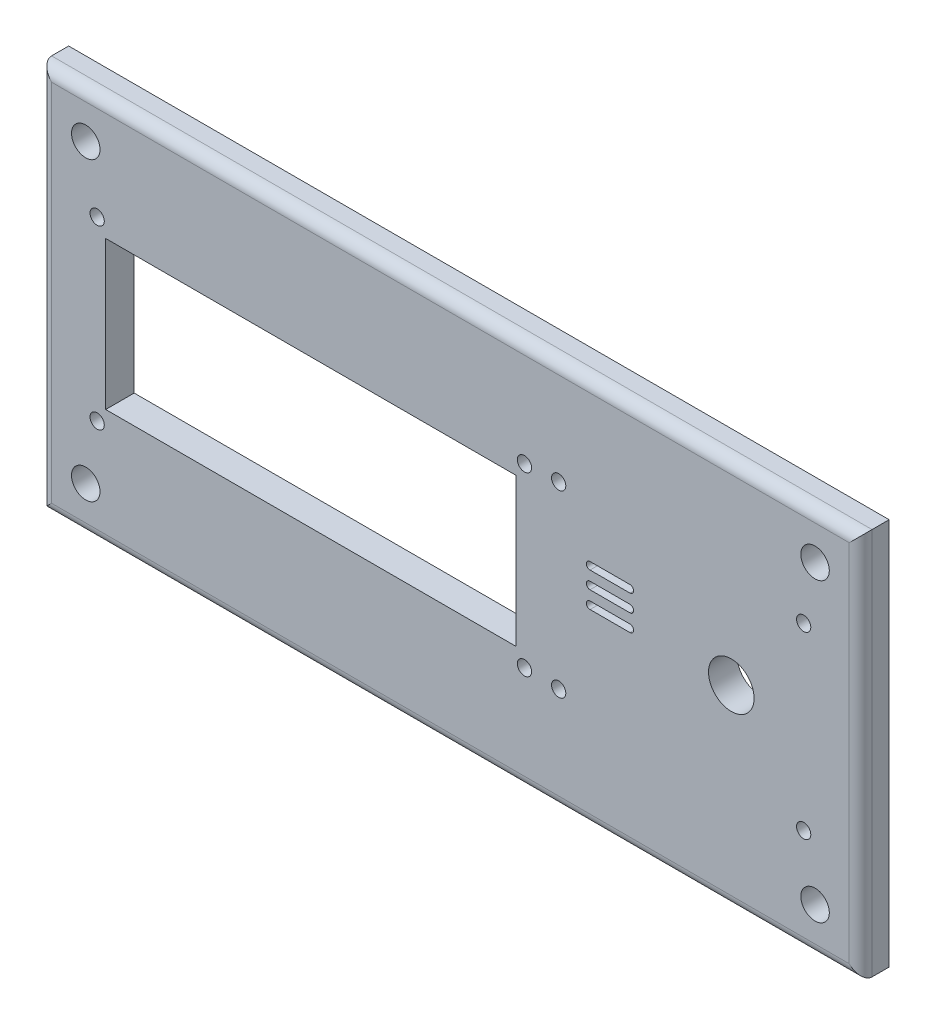
SolidWorks part; units mm, degrees
ref_plane "Спереди" through (0, 0, 0) normal (0, 0, 1) x (1, 0, 0)
ref_plane "Сверху" through (0, 0, 0) normal (0, 1, 0) x (1, 0, 0)
ref_plane "Справа" through (0, 0, 0) normal (1, 0, 0) x (0, 0, -1)
sketch "Эскиз1" plane through (0, 0, 0) normal (0, 0, 1) x (1, 0, 0)
  line L1 (-68.9586, 25.5843) -> (75.0414, 25.5843)
  line L2 (-68.9586, 25.5843) -> (-68.9586, -42.4157)
  line L3 (-68.9586, -42.4157) -> (75.0414, -42.4157)
  line L4 (75.0414, 25.5843) -> (75.0414, -42.4157)
  dimension "D1" = 144
  dimension "D2" = 68
extrude "Бобышка-Вытянуть1" add sketch "Эскиз1" along normal blind 5
sketch "Эскиз2" plane through (0, 0, 5) normal (0, 0, 1) x (1, 0, 0)
  line L0 (75.0414, 25.5843) -> (-68.9586, 25.5843) construction
  line L3 (-68.9586, 25.5843) -> (-68.9586, -42.4157) construction
  circle A0 centre (-58.9586, 7.0843) radius 1.25
  circle A1 centre (-58.9586, -23.9157) radius 1.25
  circle A2 centre (16.0414, 7.0843) radius 1.25
  circle A3 centre (16.0414, -23.9157) radius 1.25
  dimension "D1" = 2.5
  dimension "D2" = 2.5
  dimension "D3" = 2.5
  dimension "D4" = 2.5
  dimension "D5" = 75
  dimension "D6" = 31
  dimension "D7" = 31
  dimension "D8" = 75
  dimension "D9" = 18.5
  dimension "D10" = 10
  dimension "D11" = 10
  dimension "D12" = 18.5
extrude "Вырез-Вытянуть1" cut sketch "Эскиз2" against normal through all
sketch "Эскиз3" plane through (0, 0, 5) normal (0, 0, 1) x (1, 0, 0)
  line L0 (75.0414, 25.5843) -> (-68.9586, 25.5843) construction
  line L1 (-57.4586, 4.5843) -> (14.5414, 4.5843)
  line L2 (-57.4586, 4.5843) -> (-57.4586, -21.4157)
  line L3 (-57.4586, -21.4157) -> (14.5414, -21.4157)
  line L4 (14.5414, 4.5843) -> (14.5414, -21.4157)
  circle A1 centre (16.0414, 7.0843) radius 1.25 construction
  circle A3 centre (-58.9586, -23.9157) radius 1.25 construction
  dimension "D1" = 72
  dimension "D2" = 26
  dimension "D3" = 21
  dimension "D4" = 1.5
  dimension "D5" = 1.5
extrude "Вырез-Вытянуть2" cut sketch "Эскиз3" against normal through all
sketch "Эскиз5" plane through (0, 0, 5) normal (0, 0, 1) x (1, 0, 0)
  line L0 (75.0414, 25.5843) -> (-68.9586, 25.5843) construction
  circle A0 centre (22.0414, -24.1657) radius 1.25
  circle A1 centre (65.0414, -24.1657) radius 1.25
  circle A2 centre (65.0414, 7.3343) radius 1.25
  circle A3 centre (22.0414, 7.3343) radius 1.25
  circle A4 centre (16.0414, -23.9157) radius 1.25 construction
  dimension "D1" = 2
  dimension "D4" = 2.5
  dimension "D5" = 6
  dimension "D3" = 18.25
  dimension "D2" = 2
extrude "Вырез-Вытянуть3" cut sketch "Эскиз5" against normal through all
sketch "Эскиз6" plane through (0, 0, 5) normal (0, 0, 1) x (1, 0, 0)
  line L0 (27.5414, -8.6657) -> (34.5414, -8.6657) construction
  line L1 (27.5414, -8.0167) -> (34.5414, -8.0167)
  line L2 (27.5414, -9.3146) -> (34.5414, -9.3146)
  line L3 (27.5414, -5.6657) -> (34.5414, -5.6657) construction
  line L4 (27.5414, -5.0167) -> (34.5414, -5.0167)
  line L5 (27.5414, -6.3146) -> (34.5414, -6.3146)
  line L6 (27.5414, -2.6657) -> (34.5414, -2.6657) construction
  line L7 (27.5414, -2.0167) -> (34.5414, -2.0167)
  line L8 (27.5414, -3.3146) -> (34.5414, -3.3146)
  arc A0 (27.5414, -8.0167) -> (27.5414, -9.3146) centre (27.5414, -8.6657) ccw
  arc A1 (34.5414, -9.3146) -> (34.5414, -8.0167) centre (34.5414, -8.6657) ccw
  arc A2 (27.5414, -5.0167) -> (27.5414, -6.3146) centre (27.5414, -5.6657) ccw
  arc A3 (34.5414, -6.3146) -> (34.5414, -5.0167) centre (34.5414, -5.6657) ccw
  arc A4 (27.5414, -2.0167) -> (27.5414, -3.3146) centre (27.5414, -2.6657) ccw
  arc A5 (34.5414, -3.3146) -> (34.5414, -2.0167) centre (34.5414, -2.6657) ccw
  circle A6 centre (22.0414, 7.3343) radius 1.25 construction
  point P2 (31.0414, -8.6657)
  point P10 (31.0414, -5.6657)
  point P17 (31.0414, -2.6657)
  dimension "D2" = 7
  dimension "D3" = 9
  dimension "D4" = 13
  dimension "D1" = 3
extrude "Вырез-Вытянуть4" cut sketch "Эскиз6" against normal through all
sketch "Эскиз7" plane through (0, 0, 5) normal (0, 0, 1) x (1, 0, 0)
  circle A0 centre (52.3414, -8.4157) radius 4
  circle A1 centre (65.0414, 7.3343) radius 1.25 construction
  circle A3 centre (65.0414, 7.3343) radius 1.25 construction
  dimension "D1" = 8
  dimension "D2" = 15.75
  dimension "D3" = 12.7
extrude "Вырез-Вытянуть5" cut sketch "Эскиз7" against normal through all
sketch "Эскиз8" plane through (0, 0, 5) normal (0, 0, 1) x (1, 0, 0)
  line L0 (75.0414, 25.5843) -> (-68.9586, 25.5843) construction
  line L1 (-68.9586, 25.5843) -> (-68.9586, -42.4157) construction
  line L2 (75.0414, -42.4157) -> (75.0414, 25.5843) construction
  line L3 (-68.9586, -42.4157) -> (75.0414, -42.4157) construction
  circle A0 centre (-60.9586, 17.5843) radius 2.5
  circle A1 centre (67.0414, 17.5843) radius 2.5
  circle A2 centre (67.0414, -34.4157) radius 2.5
  circle A3 centre (-60.9586, -34.4157) radius 2.5
  dimension "D1" = 5
  dimension "D2" = 5
  dimension "D3" = 5
  dimension "D4" = 5
  dimension "D5" = 8
  dimension "D6" = 8
  dimension "D7" = 8
  dimension "D8" = 8
  dimension "D9" = 8
  dimension "D10" = 8
  dimension "D11" = 8
  dimension "D12" = 8
extrude "Вырез-Вытянуть6" cut sketch "Эскиз8" against normal through all
fillet "Скругление1" radius 2 4 edges at (75.0414, -8.4157, 5) (3.0414, -42.4157, 5) (-68.9586, -8.4157, 5) (3.0414, 25.5843, 5)
